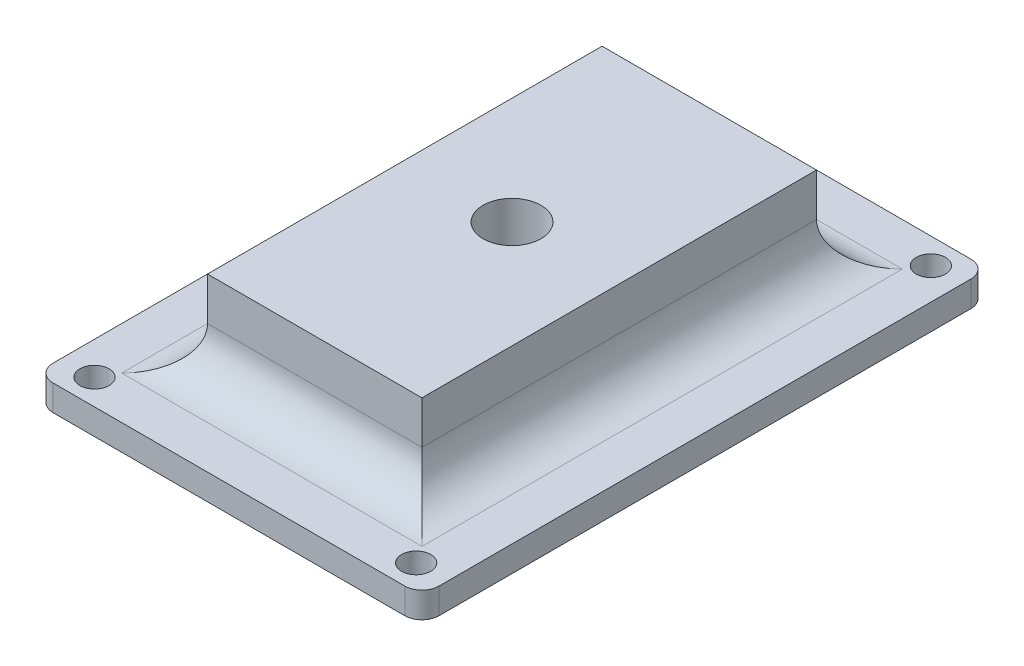
SolidWorks part; units mm, degrees
ref_plane "Alzado" through (0, 0, 0) normal (0, 0, 1) x (1, 0, 0)
ref_plane "Planta" through (0, 0, 0) normal (0, 1, 0) x (1, 0, 0)
ref_plane "Vista lateral" through (0, 0, 0) normal (1, 0, 0) x (0, 0, -1)
sketch "Croquis1" plane through (0, 95.1, 0) normal (0, 1, 0) x (1, 0, 0)
  line L0 (328.7071, -31.9645) -> (324.4645, -36.2071) construction
  line L1 (282.6716, 33) -> (327.6716, 33)
  line L2 (282.6716, 33) -> (282.6716, -33)
  line L3 (282.6716, -33) -> (327.6716, -33)
  line L4 (327.6716, 33) -> (327.6716, -33)
  line L5 (218, -31.2574) -> (218, 31.2574) construction
  arc A0 (322.75, -30) -> (325.25, -30) centre (324, -30) ccw construction
  arc A1 (325.25, -30) -> (322.75, -30) centre (324, -30) ccw construction
  arc A2 (285.25, -30) -> (287.75, -30) centre (286.5, -30) ccw construction
  arc A3 (287.75, -30) -> (285.25, -30) centre (286.5, -30) ccw construction
  arc A4 (325.25, 30) -> (322.75, 30) centre (324, 30) ccw construction
  arc A5 (322.75, 30) -> (325.25, 30) centre (324, 30) ccw construction
  arc A6 (287.75, 30) -> (285.25, 30) centre (286.5, 30) ccw construction
  arc A7 (285.25, 30) -> (287.75, 30) centre (286.5, 30) ccw construction
  arc A8 (322.75, -30) -> (325.25, -30) centre (324, -30) ccw construction
  arc A9 (325.25, -30) -> (322.75, -30) centre (324, -30) ccw construction
  arc A10 (285.25, -30) -> (287.75, -30) centre (286.5, -30) ccw construction
  arc A11 (287.75, -30) -> (285.25, -30) centre (286.5, -30) ccw construction
  arc A12 (325.25, 30) -> (322.75, 30) centre (324, 30) ccw construction
  arc A13 (322.75, 30) -> (325.25, 30) centre (324, 30) ccw construction
  arc A14 (287.75, 30) -> (285.25, 30) centre (286.5, 30) ccw construction
  arc A15 (285.25, 30) -> (287.75, 30) centre (286.5, 30) ccw construction
  arc A16 (323.15, 30) -> (324.85, 30) centre (324, 30) ccw
  arc A17 (324.85, 30) -> (323.15, 30) centre (324, 30) ccw
  arc A18 (285.65, 30) -> (287.35, 30) centre (286.5, 30) ccw
  arc A19 (287.35, 30) -> (285.65, 30) centre (286.5, 30) ccw
  arc A20 (285.65, -30) -> (287.35, -30) centre (286.5, -30) ccw
  arc A21 (287.35, -30) -> (285.65, -30) centre (286.5, -30) ccw
  arc A22 (323.15, -30) -> (324.85, -30) centre (324, -30) ccw
  arc A23 (324.85, -30) -> (323.15, -30) centre (324, -30) ccw
  point P10 (218, 0)
  point P11 (282.6716, 0)
  dimension "D1" = 66
  dimension "D2" = 45
  dimension "D3" = 0.4
extrude "Saliente-Extruir1" add sketch "Croquis1" along normal blind 3
fillet "Redondeo1" radius 2 4 edges at (282.6716, 96.6, -33) (327.6716, 96.6, -33) (282.6716, 96.6, 33) (327.6716, 96.6, 33)
sketch "Croquis2" plane through (0, 98.1, 0) normal (0, 1, 0) x (1, 0, 0)
  line L8 (317.6716, 23) -> (292.6716, 23)
  line L9 (292.6716, 23) -> (292.6716, -23)
  line L10 (292.6716, -23) -> (317.6716, -23)
  line L11 (317.6716, -23) -> (317.6716, 23)
  line L12 (317.6716, 23) -> (292.6716, 23)
  line L13 (292.6716, 23) -> (292.6716, -23)
  line L14 (292.6716, -23) -> (317.6716, -23)
  line L15 (317.6716, -23) -> (317.6716, 23)
  dimension "D1" = 10
extrude "Saliente-Extruir2" add sketch "Croquis2" along normal blind 10
fillet "Redondeo2" radius 5 2 edges at (305.1716, 98.1, -23) (305.1716, 98.1, 23)
fillet "Redondeo3" radius 5 2 edges at (292.6716, 98.1, 0) (317.6716, 98.1, 0)
sketch "Croquis3" plane through (0, 95.1, 0) normal (0, -1, 0) x (1, 0, 0)
  line L0 (282.6716, -31) -> (282.6716, 31) construction
  line L1 (284.6716, 33) -> (325.6716, 33) construction
  circle A0 centre (305.1716, 0) radius 3.125
  point P4 (282.6716, 0)
  point P7 (305.1716, 33)
  dimension "D1" = 6.25
hole_wizard "Avellanado para tornillo con cabeza ovalada de 1/41" positions "Croquis4" profile "Croquis6" countersink size "1/4" standard "Ansi Inch" end condition through all
sketch "Croquis4" plane through (0, 95.1, 0) normal (0, -1, 0) x (-1, 0, 0)
  point P0 (-305.1716, 0)
sketch "Croquis6" plane through (305.1716, 95.1, 0) normal (1, 0, 0) x (0, 0, -1)
  line L0 (0, 0) -> (0, 13)
  line L1 (0, 13) -> (3.3782, 13)
  line L2 (3.3782, 13) -> (3.3782, 3.5209)
  line L3 (3.3782, 3.5209) -> (6.4389, 0)
  line L5 (6.4389, 0) -> (0, 0)
  line L6 (-3.3782, 3.5209) -> (-6.4389, 0) construction
  line L11 (0, -6.35) -> (0, 107.95) construction
  dimension "Diámetro de taladro hasta el siguiente" = 6.7564
  dimension "Profundidad de taladro hasta el siguiente" = 13
  dimension "Diámetro de avellanado cercano" = 12.8778
  dimension "Ángulo de avellanado cercano" = 82
hole_wizard "Taladro de margen para M31" positions "Croquis7" profile "Croquis9" hole size "M3" standard "Ansi Metric" end condition through all
sketch "Croquis7" plane through (0, 98.1, 0) normal (0, 1, 0) x (1, 0, 0)
  point P0 (324, -30)
  point P3 (286.5, -30)
  point P6 (324, 30)
  point P9 (286.5, 30)
sketch "Croquis9" plane through (324, 98.1, 30) normal (1, 0, 0) x (0, 0, 1)
  line L0 (0, 0) -> (0, 3)
  line L1 (0, 3) -> (1.7, 3)
  line L2 (1.7, 3) -> (1.7, 0)
  line L5 (1.7, 0) -> (0, 0)
  line L11 (0, -6.35) -> (0, 107.95) construction
  dimension "Diámetro de taladro hasta el siguiente" = 3.4
  dimension "Profundidad de taladro hasta el siguiente" = 3
